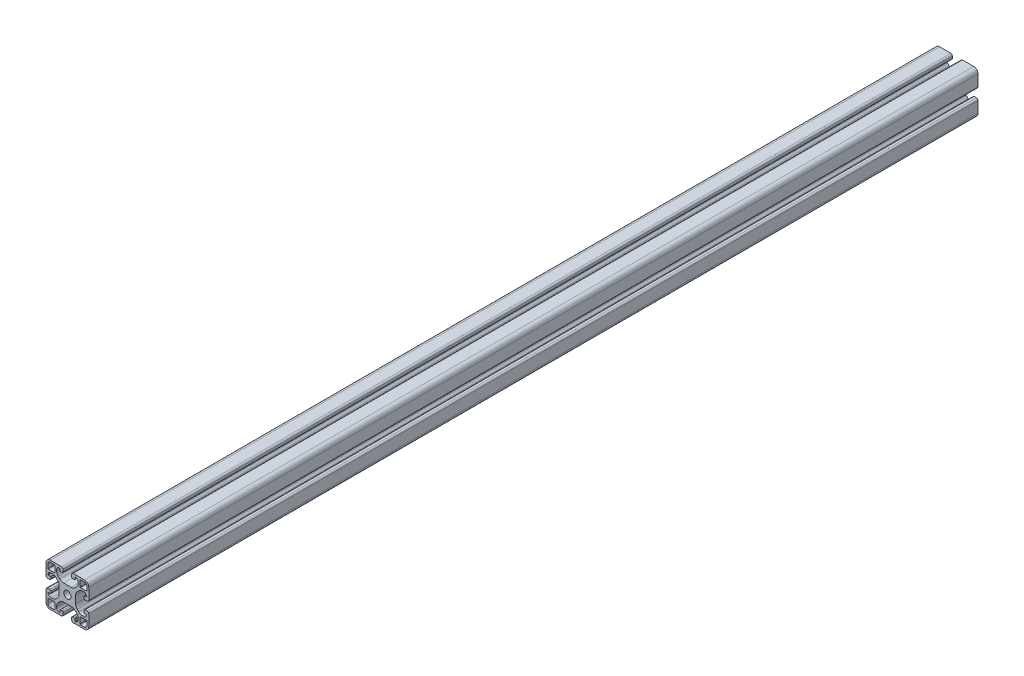
SolidWorks part; units mm, degrees
ref_plane "Plan de face" through (0, 0, 0) normal (0, 0, 1) x (1, 0, 0)
ref_plane "Plan de dessus" through (0, 0, 0) normal (0, 1, 0) x (1, 0, 0)
ref_plane "Plan de droite" through (0, 0, 0) normal (1, 0, 0) x (0, 0, -1)
ref_plane "Plan1" through (0, 0, -30) normal (0, 0, -1) x (-1, 0, 0)
sketch "Esquisse1" plane through (0, 0, -30) normal (0, 0, -1) x (-1, 0, 0)
  line L0 (-4.5, 15) -> (-4.5, 13.5)
  line L1 (-4, 13) -> (-2.5, 13)
  line L2 (-4.5, 10) -> (-5.8076, 10)
  line L3 (-9.3431, 11.4645) -> (-10.7855, 12.9069)
  line L4 (-12.25, 16.4424) -> (-12.25, 23.5576)
  line L5 (-10.7855, 27.0931) -> (-9.3431, 28.5355)
  line L6 (-5.8076, 30) -> (-4.5, 30)
  line L7 (-2.5, 27) -> (-4, 27)
  line L8 (-4.5, 26.5) -> (-4.5, 25)
  line L9 (-3.5, 24) -> (-1.5, 24)
  line L10 (0, 25.5) -> (0, 36)
  line L11 (-4, 40) -> (-14.5, 40)
  line L12 (-16, 38.5) -> (-16, 36.5)
  line L13 (-15, 35.5) -> (-13.5, 35.5)
  line L14 (-13, 36) -> (-13, 37.5)
  line L15 (-10, 35.5) -> (-10, 34.1924)
  line L16 (-11.4645, 30.6569) -> (-12.9069, 29.2145)
  line L17 (-16.4424, 27.75) -> (-23.5576, 27.75)
  line L18 (-27.0931, 29.2145) -> (-28.5355, 30.6569)
  line L19 (-30, 34.1924) -> (-30, 35.5)
  line L20 (-27, 37.5) -> (-27, 36)
  line L21 (-26.5, 35.5) -> (-25, 35.5)
  line L22 (-24, 36.5) -> (-24, 38.5)
  line L23 (-25.5, 40) -> (-36, 40)
  line L24 (-40, 36) -> (-40, 25.5)
  line L25 (-38.5, 24) -> (-36.5, 24)
  line L26 (-35.5, 25) -> (-35.5, 26.5)
  line L27 (-36, 27) -> (-37.5, 27)
  line L28 (-35.5, 30) -> (-34.1924, 30)
  line L29 (-30.6569, 28.5355) -> (-29.2145, 27.0931)
  line L30 (-27.75, 23.5576) -> (-27.75, 16.4424)
  line L31 (-29.2145, 12.9069) -> (-30.6569, 11.4645)
  line L32 (-34.1924, 10) -> (-35.5, 10)
  line L33 (-37.5, 13) -> (-36, 13)
  line L34 (-35.5, 13.5) -> (-35.5, 15)
  line L35 (-36.5, 16) -> (-38.5, 16)
  line L36 (-40, 14.5) -> (-40, 4)
  line L37 (-36, 0) -> (-25.5, 0)
  line L38 (-24, 1.5) -> (-24, 3.5)
  line L39 (-25, 4.5) -> (-26.5, 4.5)
  line L40 (-27, 4) -> (-27, 2.5)
  line L41 (-30, 4.5) -> (-30, 5.8076)
  line L42 (-28.5355, 9.3431) -> (-27.0931, 10.7855)
  line L43 (-23.5576, 12.25) -> (-16.4424, 12.25)
  line L44 (-12.9069, 10.7855) -> (-11.4645, 9.3431)
  line L45 (-10, 5.8076) -> (-10, 4.5)
  line L46 (-13, 2.5) -> (-13, 4)
  line L47 (-13.5, 4.5) -> (-15, 4.5)
  line L48 (-16, 3.5) -> (-16, 1.5)
  line L49 (-14.5, 0) -> (-4, 0)
  line L50 (0, 4) -> (0, 14.5)
  line L51 (-1.5, 16) -> (-3.5, 16)
  line L52 (-4, 1.8) -> (-7.7, 1.8)
  line L53 (-8.2, 2.3) -> (-8.2, 7.7)
  line L54 (-7.7, 8.2) -> (-2.3, 8.2)
  line L55 (-1.8, 7.7) -> (-1.8, 4)
  line L56 (-38.2, 4) -> (-38.2, 7.7)
  line L57 (-37.7, 8.2) -> (-32.3, 8.2)
  line L58 (-31.8, 7.7) -> (-31.8, 2.3)
  line L59 (-32.3, 1.8) -> (-36, 1.8)
  line L60 (-36, 38.2) -> (-32.3, 38.2)
  line L61 (-31.8, 37.7) -> (-31.8, 32.3)
  line L62 (-32.3, 31.8) -> (-37.7, 31.8)
  line L63 (-38.2, 32.3) -> (-38.2, 36)
  line L64 (-1.8, 36) -> (-1.8, 32.3)
  line L65 (-2.3, 31.8) -> (-7.7, 31.8)
  line L66 (-8.2, 32.3) -> (-8.2, 37.7)
  line L67 (-7.7, 38.2) -> (-4, 38.2)
  arc A0 (-4.5, 13.5) -> (-4, 13) centre (-4, 13.5) ccw
  arc A1 (-2.5, 13) -> (-2, 12.5) centre (-2.5, 12.5) cw
  arc A2 (-2, 12.5) -> (-4.5, 10) centre (-4.5, 12.5) cw
  arc A3 (-5.8076, 10) -> (-9.3431, 11.4645) centre (-5.8076, 15) cw
  arc A4 (-10.7855, 12.9069) -> (-12.25, 16.4424) centre (-7.25, 16.4424) cw
  arc A5 (-12.25, 23.5576) -> (-10.7855, 27.0931) centre (-7.25, 23.5576) cw
  arc A6 (-9.3431, 28.5355) -> (-5.8076, 30) centre (-5.8076, 25) cw
  arc A7 (-4.5, 30) -> (-2, 27.5) centre (-4.5, 27.5) cw
  arc A8 (-2, 27.5) -> (-2.5, 27) centre (-2.5, 27.5) cw
  arc A9 (-4, 27) -> (-4.5, 26.5) centre (-4, 26.5) ccw
  arc A10 (-4.5, 25) -> (-3.5, 24) centre (-3.5, 25) ccw
  arc A11 (-1.5, 24) -> (0, 25.5) centre (-1.5, 25.5) ccw
  arc A12 (0, 36) -> (-4, 40) centre (-4, 36) ccw
  arc A13 (-14.5, 40) -> (-16, 38.5) centre (-14.5, 38.5) ccw
  arc A14 (-16, 36.5) -> (-15, 35.5) centre (-15, 36.5) ccw
  arc A15 (-13.5, 35.5) -> (-13, 36) centre (-13.5, 36) ccw
  arc A16 (-13, 37.5) -> (-12.5, 38) centre (-12.5, 37.5) cw
  arc A17 (-12.5, 38) -> (-10, 35.5) centre (-12.5, 35.5) cw
  arc A18 (-10, 34.1924) -> (-11.4645, 30.6569) centre (-15, 34.1924) cw
  arc A19 (-12.9069, 29.2145) -> (-16.4424, 27.75) centre (-16.4424, 32.75) cw
  arc A20 (-23.5576, 27.75) -> (-27.0931, 29.2145) centre (-23.5576, 32.75) cw
  arc A21 (-28.5355, 30.6569) -> (-30, 34.1924) centre (-25, 34.1924) cw
  arc A22 (-30, 35.5) -> (-27.5, 38) centre (-27.5, 35.5) cw
  arc A23 (-27.5, 38) -> (-27, 37.5) centre (-27.5, 37.5) cw
  arc A24 (-27, 36) -> (-26.5, 35.5) centre (-26.5, 36) ccw
  arc A25 (-25, 35.5) -> (-24, 36.5) centre (-25, 36.5) ccw
  arc A26 (-24, 38.5) -> (-25.5, 40) centre (-25.5, 38.5) ccw
  arc A27 (-36, 40) -> (-40, 36) centre (-36, 36) ccw
  arc A28 (-40, 25.5) -> (-38.5, 24) centre (-38.5, 25.5) ccw
  arc A29 (-36.5, 24) -> (-35.5, 25) centre (-36.5, 25) ccw
  arc A30 (-35.5, 26.5) -> (-36, 27) centre (-36, 26.5) ccw
  arc A31 (-37.5, 27) -> (-38, 27.5) centre (-37.5, 27.5) cw
  arc A32 (-38, 27.5) -> (-35.5, 30) centre (-35.5, 27.5) cw
  arc A33 (-34.1924, 30) -> (-30.6569, 28.5355) centre (-34.1924, 25) cw
  arc A34 (-29.2145, 27.0931) -> (-27.75, 23.5576) centre (-32.75, 23.5576) cw
  arc A35 (-27.75, 16.4424) -> (-29.2145, 12.9069) centre (-32.75, 16.4424) cw
  arc A36 (-30.6569, 11.4645) -> (-34.1924, 10) centre (-34.1924, 15) cw
  arc A37 (-35.5, 10) -> (-38, 12.5) centre (-35.5, 12.5) cw
  arc A38 (-38, 12.5) -> (-37.5, 13) centre (-37.5, 12.5) cw
  arc A39 (-36, 13) -> (-35.5, 13.5) centre (-36, 13.5) ccw
  arc A40 (-35.5, 15) -> (-36.5, 16) centre (-36.5, 15) ccw
  arc A41 (-38.5, 16) -> (-40, 14.5) centre (-38.5, 14.5) ccw
  arc A42 (-40, 4) -> (-36, 0) centre (-36, 4) ccw
  arc A43 (-25.5, 0) -> (-24, 1.5) centre (-25.5, 1.5) ccw
  arc A44 (-24, 3.5) -> (-25, 4.5) centre (-25, 3.5) ccw
  arc A45 (-26.5, 4.5) -> (-27, 4) centre (-26.5, 4) ccw
  arc A46 (-27, 2.5) -> (-27.5, 2) centre (-27.5, 2.5) cw
  arc A47 (-27.5, 2) -> (-30, 4.5) centre (-27.5, 4.5) cw
  arc A48 (-30, 5.8076) -> (-28.5355, 9.3431) centre (-25, 5.8076) cw
  arc A49 (-27.0931, 10.7855) -> (-23.5576, 12.25) centre (-23.5576, 7.25) cw
  arc A50 (-16.4424, 12.25) -> (-12.9069, 10.7855) centre (-16.4424, 7.25) cw
  arc A51 (-11.4645, 9.3431) -> (-10, 5.8076) centre (-15, 5.8076) cw
  arc A52 (-10, 4.5) -> (-12.5, 2) centre (-12.5, 4.5) cw
  arc A53 (-12.5, 2) -> (-13, 2.5) centre (-12.5, 2.5) cw
  arc A54 (-13, 4) -> (-13.5, 4.5) centre (-13.5, 4) ccw
  arc A55 (-15, 4.5) -> (-16, 3.5) centre (-15, 3.5) ccw
  arc A56 (-16, 1.5) -> (-14.5, 0) centre (-14.5, 1.5) ccw
  arc A57 (-4, 0) -> (0, 4) centre (-4, 4) ccw
  arc A58 (0, 14.5) -> (-1.5, 16) centre (-1.5, 14.5) ccw
  arc A59 (-3.5, 16) -> (-4.5, 15) centre (-3.5, 15) ccw
  circle A60 centre (-20, 20) radius 3.4
  arc A61 (-1.8, 4) -> (-4, 1.8) centre (-4, 4) cw
  arc A62 (-7.7, 1.8) -> (-8.2, 2.3) centre (-7.7, 2.3) cw
  arc A63 (-8.2, 7.7) -> (-7.7, 8.2) centre (-7.7, 7.7) cw
  arc A64 (-2.3, 8.2) -> (-1.8, 7.7) centre (-2.3, 7.7) cw
  arc A65 (-36, 1.8) -> (-38.2, 4) centre (-36, 4) cw
  arc A66 (-38.2, 7.7) -> (-37.7, 8.2) centre (-37.7, 7.7) cw
  arc A67 (-32.3, 8.2) -> (-31.8, 7.7) centre (-32.3, 7.7) cw
  arc A68 (-31.8, 2.3) -> (-32.3, 1.8) centre (-32.3, 2.3) cw
  arc A69 (-38.2, 36) -> (-36, 38.2) centre (-36, 36) cw
  arc A70 (-32.3, 38.2) -> (-31.8, 37.7) centre (-32.3, 37.7) cw
  arc A71 (-31.8, 32.3) -> (-32.3, 31.8) centre (-32.3, 32.3) cw
  arc A72 (-37.7, 31.8) -> (-38.2, 32.3) centre (-37.7, 32.3) cw
  arc A73 (-4, 38.2) -> (-1.8, 36) centre (-4, 36) cw
  arc A74 (-1.8, 32.3) -> (-2.3, 31.8) centre (-2.3, 32.3) cw
  arc A75 (-7.7, 31.8) -> (-8.2, 32.3) centre (-7.7, 32.3) cw
  arc A76 (-8.2, 37.7) -> (-7.7, 38.2) centre (-7.7, 37.7) cw
extrude "Boss.-Extru.1" add sketch "Esquisse1" against normal blind 832
